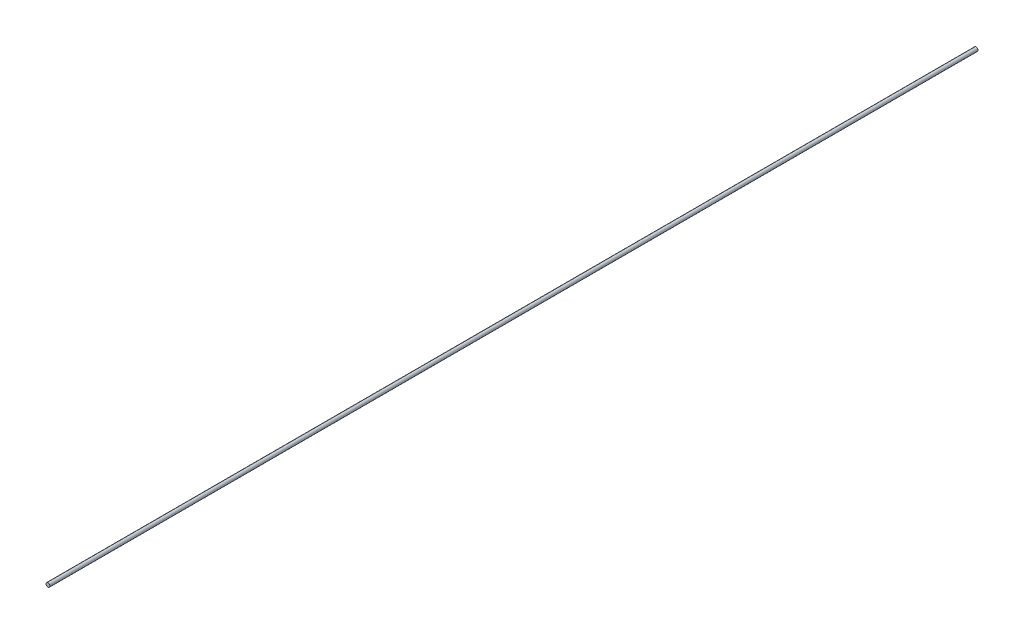
SolidWorks part; units mm, degrees
material "AISI 316 Stainless Steel Sheet (SS)"
ref_plane "Front Plane" through (0, 0, 0) normal (0, 0, 1) x (1, 0, 0)
ref_plane "Top Plane" through (0, 0, 0) normal (0, 1, 0) x (1, 0, 0)
ref_plane "Right Plane" through (0, 0, 0) normal (1, 0, 0) x (0, 0, -1)
sketch "Sketch1" plane through (0, 0, 0) normal (0, 0, 1) x (1, 0, 0)
  circle A0 centre (0, 0) radius 1.5875
  dimension "D1" = 3.175
extrude "Boss-Extrude1" add sketch "Sketch1" along normal blind 762
